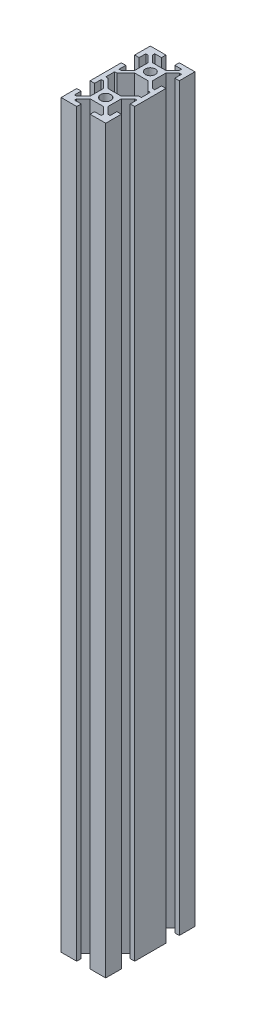
SolidWorks part; units mm, degrees
ref_plane "Front Plane" through (0, 0, 0) normal (0, 0, 1) x (1, 0, 0)
ref_plane "Top Plane" through (0, 0, 0) normal (0, 1, 0) x (1, 0, 0)
ref_plane "Right Plane" through (0, 0, 0) normal (1, 0, 0) x (0, 0, -1)
sketch "Sketch1" plane through (0, 0, 0) normal (0, 1, 0) x (1, 0, 0)
  line L0 (10, 6.326) -> (10, -39.1326) construction
  line L4 (20, 0) -> (20, -7)
  line L5 (-2.6965, -10) -> (22.6965, -10) construction
  line L6 (-2.6965, -30) -> (22.6965, -30) construction
  line L7 (2, -4) -> (2, -7)
  line L9 (18, -4) -> (18, -7)
  line L10 (4, -2) -> (7, -2)
  line L11 (7, 0) -> (7, -2)
  line L12 (7, -6) -> (13, -6)
  line L13 (6, -7) -> (6, -13)
  line L14 (7, -14) -> (13, -14)
  line L15 (14, -7) -> (14, -13)
  line L16 (6, -6) -> (14, -14) construction
  line L17 (6, -14) -> (14, -6) construction
  line L18 (7, -26) -> (13, -26)
  line L19 (6, -27) -> (6, -33)
  line L20 (7, -34) -> (13, -34)
  line L21 (14, -27) -> (14, -33)
  line L22 (6, -26) -> (14, -34) construction
  line L23 (6, -34) -> (14, -26) construction
  line L24 (13, 0) -> (13, -2)
  line L25 (13, 0) -> (20, 0)
  line L26 (13, -2) -> (16, -2)
  line L27 (0, 0) -> (20, 0) construction
  line L28 (0, -7) -> (2, -7)
  line L29 (2, -2) -> (18, -2) construction
  line L30 (18, -7) -> (20, -7)
  line L31 (6, -7) -> (3, -4)
  line L32 (14, -7) -> (17, -4)
  line L33 (13, -6) -> (16, -3)
  line L34 (18, -2) -> (18, -38) construction
  line L35 (7, -6) -> (4, -3)
  line L36 (23.1857, -20) -> (-3.1857, -20) construction
  line L37 (2, -2) -> (2, -38) construction
  line L38 (14, -13) -> (17, -16)
  line L39 (13, -14) -> (17, -18)
  line L40 (7, -14) -> (3, -18)
  line L41 (6, -13) -> (3, -16)
  line L42 (3, -18) -> (2, -18)
  line L43 (17, -18) -> (18, -18)
  line L44 (2, -18) -> (2, -22)
  line L45 (18, -18) -> (18, -22)
  line L46 (0, -13) -> (2, -13)
  line L47 (18, -13) -> (20, -13)
  line L48 (0, -13) -> (0, -27)
  line L49 (2, -13) -> (2, -16)
  line L50 (0, 0) -> (0, -40) construction
  line L51 (18, -13) -> (18, -16)
  line L52 (20, -13) -> (20, -27)
  line L53 (2, -16) -> (3, -16)
  line L54 (20, 0) -> (20, -40) construction
  line L55 (18, -16) -> (17, -16)
  line L56 (0, 0) -> (7, 0)
  line L59 (2, -4) -> (3, -4)
  line L60 (4, -2) -> (4, -3)
  line L61 (0, 0) -> (0, -7)
  line L62 (18, -4) -> (17, -4)
  line L63 (16, -2) -> (16, -3)
  line L66 (7, -26) -> (3, -22)
  line L67 (2, -38) -> (18, -38) construction
  line L68 (0, -40) -> (20, -40) construction
  line L69 (13, -26) -> (17, -22)
  line L70 (17, -22) -> (18, -22)
  line L71 (2, -24) -> (2, -27)
  line L72 (18, -27) -> (20, -27)
  line L73 (18, -27) -> (18, -24)
  line L74 (18, -24) -> (17, -24)
  line L75 (14, -27) -> (17, -24)
  line L76 (14, -33) -> (17, -36)
  line L77 (18, -36) -> (17, -36)
  line L78 (18, -36) -> (18, -33)
  line L79 (18, -33) -> (20, -33)
  line L80 (20, -40) -> (20, -33)
  line L81 (13, -40) -> (20, -40)
  line L82 (13, -40) -> (13, -38)
  line L83 (13, -38) -> (16, -38)
  line L84 (16, -38) -> (16, -37)
  line L85 (13, -34) -> (16, -37)
  line L86 (7, -34) -> (4, -37)
  line L87 (4, -38) -> (4, -37)
  line L88 (4, -38) -> (7, -38)
  line L89 (7, -40) -> (7, -38)
  line L90 (0, -40) -> (7, -40)
  line L91 (0, -40) -> (0, -33)
  line L92 (0, -33) -> (2, -33)
  line L93 (2, -36) -> (2, -33)
  line L94 (2, -36) -> (3, -36)
  line L95 (6, -33) -> (3, -36)
  line L96 (6, -27) -> (3, -24)
  line L97 (2, -24) -> (3, -24)
  line L98 (2, -27) -> (2, -24)
  line L99 (0, -27) -> (2, -27)
  line L100 (3, -22) -> (2, -22)
  line L101 (18, -24) -> (18, -27)
  circle A0 centre (10, -10) radius 2.2132
  circle A1 centre (10, -30) radius 2.2889
  point P10 (10, -10)
  point P13 (10, -30)
  point P38 (18.5, -2.5)
  point P40 (17.5, -1.5)
  point P50 (10, -20)
  dimension "D1" = 20
  dimension "D6" = 8
  dimension "D7" = 8
  dimension "D8" = 8
  dimension "D9" = 8
  dimension "D11" = 7
  dimension "D13" = 7
  dimension "D16" = 1
  dimension "D17" = 1
  dimension "D18" = 6
  dimension "D19" = 6
  dimension "D20" = 1
  dimension "D3" = 7
  dimension "D5" = 2
extrude "Boss-Extrude1" add sketch "Sketch1" along normal blind 332 contours L48 L99 L71 L97 L96 L19 L95 L94 L93 L92 L91 L90 L89 L88 L87 L86 L20 L85 L84 L83 L82 L81 L80 L79 L78 L77 L76 L21 L75 L74 L73 L72 L52 L47 L51 L55 L38 L15 L32 L62 L9 L30 L4 L25 L24 L26 L63 L33 L12 L35 L60
equation "\"D7@Sketch1\"=\"D6@Sketch1\""
equation "\"D9@Sketch1\"=\"D8@Sketch1\""
